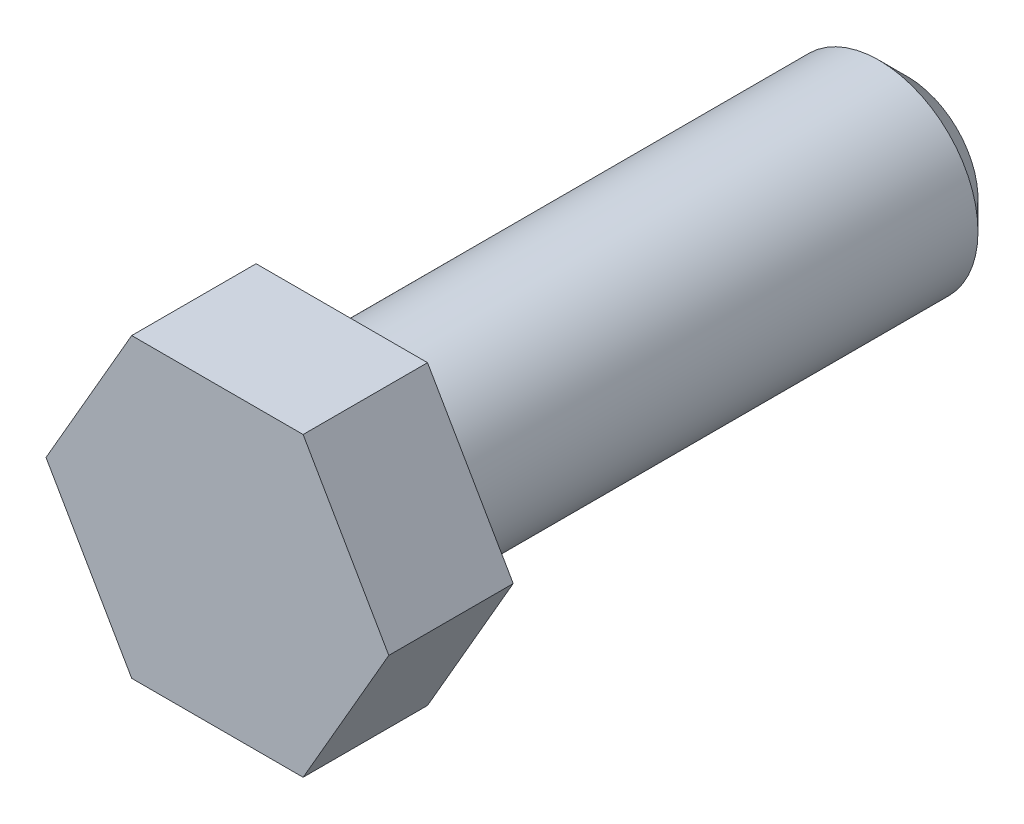
SolidWorks part; units mm, degrees
ref_plane "Plane1" through (0, 0, 0) normal (0, 0, 1) x (1, 0, 0)
ref_plane "MSC_PF1" through (0, 0, 0) normal (0, 1, 0) x (1, 0, 0)
ref_plane "Plane3" through (0, 0, 0) normal (1, 0, 0) x (0, 0, -1)
sketch "Sketch1" plane through (0, 0, 0) normal (0, 0, 1) x (1, 0, 0)
  line L0 (0, 0) -> (1, 0) construction
  line L1 (-6.0622, 10.5) -> (6.0622, 10.5)
  line L2 (-6.0622, -10.5) -> (6.0622, -10.5)
  line L3 (6.0622, 10.5) -> (12.1244, 0)
  line L4 (12.1244, 0) -> (6.0622, -10.5)
  line L5 (-6.0622, 10.5) -> (-12.1244, 0)
  line L6 (-12.1244, 0) -> (-6.0622, -10.5)
  circle A0 centre (0, 0) radius 10.5 construction
  dimension "s" = 21
extrude "Base-Extrude" add sketch "Sketch1" along normal blind 8.8
sketch "Sketch3" plane through (0, 0, 0) normal (0, 0, -1) x (-1, 0, 0)
  circle A0 centre (0, 0) radius 7
  dimension "_d" = 14
extrude "Boss-Extrude1" add sketch "Sketch3" along normal blind 40
cosmetic thread "Условное изображение резьбы2" parameters "D2"=12
chamfer "Chamfer1" distance 2 angle 45 1 edges at (-7, 0, -40)
